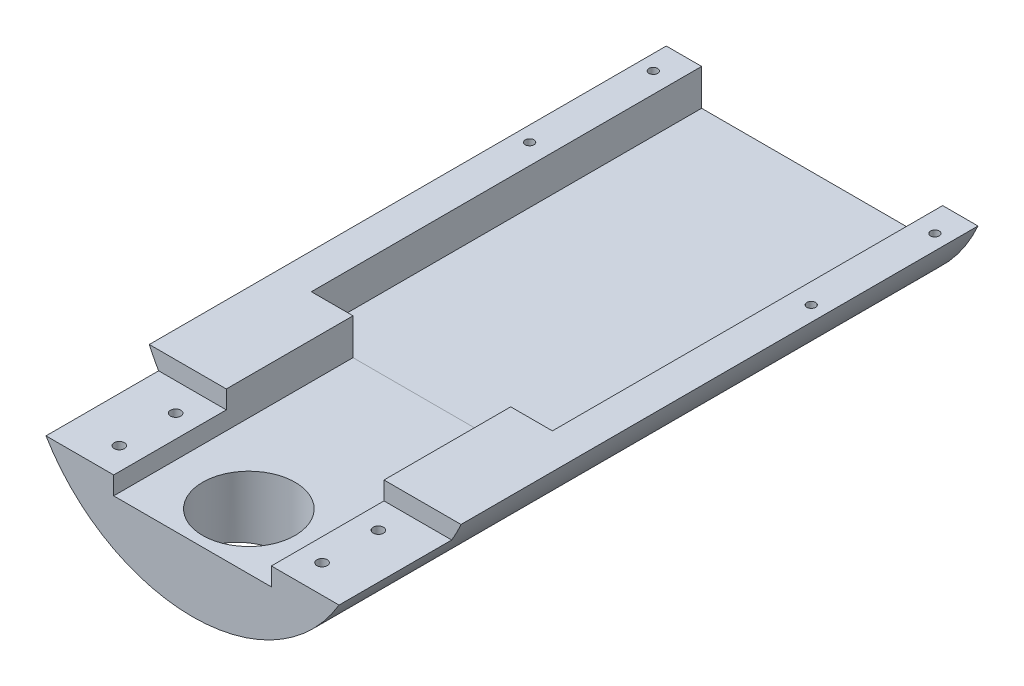
SolidWorks part; units mm, degrees
material "eSUN PLA+ (Not accurate)"
ref_plane "Front Plane" through (0, 0, 0) normal (0, 0, 1) x (1, 0, 0)
ref_plane "Top Plane" through (0, 0, 0) normal (0, 1, 0) x (1, 0, 0)
ref_plane "Right Plane" through (0, 0, 0) normal (1, 0, 0) x (0, 0, -1)
sketch "Sketch1" plane through (0, 0, 0) normal (0, 0, 1) x (1, 0, 0)
  line L0 (-69.1908, -30.525) -> (-35, -30.525)
  line L1 (-35, -30.525) -> (-35, -46.625)
  line L2 (-35, -46.625) -> (35, -46.625)
  line L3 (35, -46.625) -> (35, -30.525)
  line L4 (35, -30.525) -> (69.1908, -30.525)
  circle A0 centre (0, 0) radius 75.625 construction
  arc A1 (-69.1908, -30.525) -> (69.1908, -30.525) centre (0, 0) ccw
  point P10 (0, -75.625)
  dimension "D1" = 151.25
  dimension "D2" = 70
  dimension "D3" = 29
  dimension "D4" = 16.1
extrude "Boss-Extrude1" add sketch "Sketch1" along normal blind 279.5 from offset 15
sketch "Sketch2" plane through (0, 0, 294.5) normal (0, 0, 1) x (1, 0, 0)
  line L0 (-35, -30.525) -> (-35, -38.575) construction
  line L1 (-35, -46.625) -> (-35, -30.525) construction
  line L2 (-35, -38.575) -> (-35, -46.625) construction
  line L3 (-35, -30.525) -> (-35, -38.575)
  line L6 (-35, -38.575) -> (-65.047, -38.575)
  line L8 (-69.1908, -30.525) -> (-35, -30.525)
  arc A0 (-69.1908, -30.525) -> (-65.047, -38.575) centre (0, 0) ccw
  arc A2 (-69.1908, -30.525) -> (69.1908, -30.525) centre (0, 0) ccw construction
sketch "Sketch3" plane through (0, 0, 15) normal (0, 0, -1) x (-1, 0, 0)
  line L0 (-35, -46.625) -> (35, -46.625) construction
  line L1 (53.5, 46.625) -> (-53.5, 46.625)
  line L2 (53.5, 46.625) -> (53.5, -46.625)
  line L3 (53.5, -46.625) -> (-53.5, -46.625)
  line L4 (-53.5, 46.625) -> (-53.5, -46.625)
  line L5 (53.5, 46.625) -> (-53.5, -46.625) construction
  line L6 (53.5, -46.625) -> (-53.5, 46.625) construction
  point P0 (0, 0)
  dimension "D1" = 107
extrude "Cut-Extrude1" cut sketch "Sketch3" against normal blind 173.25
sketch "Sketch4" plane through (0, -46.625, 0) normal (0, 1, 0) x (1, 0, 0)
  line L1 (0, -15) -> (0, -294.5) construction
  line L2 (53.5, -15) -> (-53.5, -15) construction
  line L3 (35, -294.5) -> (-35, -294.5) construction
  circle A0 centre (0, -269.5) radius 20.5
  dimension "D1" = 41
  dimension "D2" = 25
extrude "Cut-Extrude2" cut sketch "Sketch4" against normal through all
extrude "Cut-Extrude3" cut sketch "Sketch2" against normal blind 50
sketch "Sketch6" plane through (0, 0, 294.5) normal (0, 0, 1) x (1, 0, 0)
  line L0 (-42.2865, -46.625) -> (-59.542, -46.625)
  line L1 (-59.542, -46.625) -> (-42.2865, -46.625)
  line L2 (-42.2865, -46.625) -> (-42.2865, -62.6976)
  arc A0 (-59.542, -46.625) -> (-42.2865, -62.6976) centre (0, 0) ccw
  arc A1 (-65.047, -38.575) -> (69.1908, -30.525) centre (0, 0) ccw construction
mirror "Mirror1" about plane through (0, 0, 0) normal (1, 0, 0) of "Cut-Extrude3"
sketch "Sketch7" plane through (0, -38.575, 0) normal (0, 1, 0) x (1, 0, 0)
  line L1 (35, -269.5) -> (65.047, -269.5) construction
  line L4 (35, -294.5) -> (65.047, -294.5)
  line L5 (65.047, -294.5) -> (65.047, -244.5)
  line L6 (65.047, -244.5) -> (35, -244.5)
  line L7 (35, -244.5) -> (35, -294.5)
  line L8 (35, -294.5) -> (65.047, -294.5) construction
  line L9 (65.047, -294.5) -> (65.047, -244.5) construction
  line L10 (65.047, -244.5) -> (35, -244.5) construction
  line L11 (35, -244.5) -> (35, -294.5) construction
  circle A0 centre (45, -257) radius 2.3
  circle A1 centre (45, -282) radius 2.3
  dimension "D2" = 4.6
  dimension "D3" = 25
  dimension "D4" = 10
  dimension "D1" = 0
extrude "Cut-Extrude5" cut sketch "Sketch7" against normal through all
mirror "Mirror2" about plane through (0, 0, 0) normal (1, 0, 0) of "Cut-Extrude5"
ref_plane "Plane1" through (0, -52.075, 0) normal (0, 1, 0) x (1, 0, 0)
sketch "Sketch11" plane through (0, -52.075, 0) normal (0, 1, 0) x (1, 0, 0)
  circle A0 centre (45, -257) radius 2.3 construction
  circle A1 centre (45, -282) radius 2.3 construction
  circle A2 centre (45, -257) radius 2.3 construction
  circle A3 centre (45, -282) radius 2.3 construction
  circle A4 centre (45, -282) radius 3.8
  circle A5 centre (45, -257) radius 3.8
  dimension "D1" = 7.6
ref_plane "Plane2" through (0, 0, 154.5) normal (0, 0, 1) x (1, 0, 0)
other "Intersect1" [suppressed]
move or copy body "Body-Convert to Mesh Body2" [suppressed] bodies to move or copy 114 copy no translate (0, 0, 0)
sketch "Sketch13" plane through (0, -46.625, 0) normal (0, 1, 0) x (1, 0, 0)
  line L0 (35, -188.25) -> (-35, -188.25)
  line L1 (-35, -294.5) -> (-35, -188.25) construction
  line L2 (-35, -188.25) -> (-53.5, -188.25) construction
split line "Split Line1"
extrude "Cut-Extrude8" cut sketch "Sketch11" along normal blind 7 and the other way through all
mirror "Mirror3" about plane through (0, 0, 0) normal (1, 0, 0) of "Cut-Extrude8"
sketch "Sketch14" plane through (0, -30.525, 0) normal (0, 1, 0) x (1, 0, 0)
  circle A0 centre (62.5, -82.35) radius 1.875 construction
  circle A1 centre (62.5, -27.45) radius 1.875 construction
  circle A2 centre (62.5, -82.35) radius 1.875 construction
  circle A3 centre (62.5, -27.45) radius 1.875 construction
  circle A5 centre (62.5, -27.45) radius 1.93
  circle A6 centre (62.5, -82.35) radius 1.93
  dimension "D1" = 3.86
extrude "Cut-Extrude9" cut sketch "Sketch14" against normal blind 7.25
mirror "Mirror4" about plane through (0, 0, 0) normal (1, 0, 0) of "Cut-Extrude9"
ref_plane "Plane3" through (0, 0, 87) normal (0, 0, 1) x (1, 0, 0)
other "Intersect2" [suppressed]
move or copy body "Body-Convert to Mesh Body3" [suppressed] bodies to move or copy 122 copy no translate (0, 0, 0) parameters "D1"=0, "D2"=0, "D3"=0
sketch "Sketch18" plane through (0, 0, 15) normal (0, 0, -1) x (-1, 0, 0)
  line L0 (0, -56.625) -> (0, -46.625)
  line L1 (0, -75.625) -> (0, -56.625) construction
  line L4 (-53.5, -46.625) -> (53.5, -46.625) construction
  line L13 (42.2078, -56.625) -> (-42.2078, -56.625)
  line L14 (42.2078, -56.625) -> (-42.2078, -56.625)
  line L17 (-44.3364, -50.125) -> (44.3364, -50.125)
  line L19 (44.3364, -56.125) -> (-44.3364, -56.125)
  line L20 (-44.3364, -56.125) -> (-44.3364, -50.125)
  line L21 (44.3364, -56.125) -> (44.3364, -50.125)
  line L27 (28.4868, -64.625) -> (-28.4868, -64.625) construction
  line L28 (30.1174, -64.625) -> (-30.1174, -64.625)
  arc A0 (-44.3364, -56.125) -> (44.3364, -56.125) centre (0, 1.8987) ccw
  arc A12 (-42.2078, -56.625) -> (42.2078, -56.625) centre (0, 0) ccw
  arc A15 (-42.2078, -56.625) -> (42.2078, -56.625) centre (0, 0) ccw
  arc A26 (-69.1908, -30.525) -> (69.1908, -30.525) centre (0, 0) ccw construction
  point P3 (0, -71.125)
  point P4 (0, -70.625)
  dimension "D6" = 0.5
  dimension "D7" = 1.8987
  dimension "D8" = 0.5
  dimension "D9" = 6
  dimension "D3" = 0
extrude "Cut-Extrude10" cut sketch "Sketch18" against normal blind 125.5 contours L20 L19 L0 L17 | L19 L21 L17 L0 | L1 L28 A15 L14 | L28 L1 L14 A15 | A15 L28 A0 L19 L0 L14 | A15 L14 L0 L19 A0 L28
ref_plane "Plane4" through (0, 0, 40) normal (0, 0, -1) x (-1, 0, 0)
sketch "Sketch19" plane through (0, 0, 40) normal (0, 0, -1) x (-1, 0, 0)
  line L0 (30.1174, -64.625) -> (-30.1174, -64.625) construction
  line L1 (30.1174, -64.625) -> (-30.1174, -64.625)
  arc A0 (-44.3364, -56.125) -> (44.3364, -56.125) centre (0, 1.8987) ccw construction
  arc A1 (-44.3364, -56.125) -> (44.3364, -56.125) centre (0, 1.8987) ccw
extrude "Cut-Extrude12" cut sketch "Sketch19" against normal blind 100.5 contours L1 A1
ref_plane "Plane5" through (0, 0, 65) normal (0, 0, -1) x (-1, 0, 0)
sketch "Sketch20" plane through (0, 0, 65) normal (0, 0, -1) x (-1, 0, 0)
  line L0 (-44.3364, -56.125) -> (-44.3364, -50.125) construction
  line L1 (44.3364, -56.125) -> (-44.3364, -56.125) construction
  line L2 (44.3364, -56.125) -> (44.3364, -50.125) construction
  line L3 (-44.3364, -50.125) -> (44.3364, -50.125) construction
  line L4 (-44.3364, -56.125) -> (-44.3364, -50.125)
  line L5 (44.3364, -56.125) -> (-44.3364, -56.125)
  line L6 (44.3364, -56.125) -> (44.3364, -50.125)
  line L7 (-44.3364, -50.125) -> (44.3364, -50.125)
extrude "Boss-Extrude2" add sketch "Sketch20" against normal up to surface (75.5 mm away) up to face at (0, -56.875, 140.5)
sketch "screw head hole" plane through (0, 0, 15) normal (0, 0, -1) x (-1, 0, 0)
  circle A0 centre (0, -68.825) radius 1.45 construction
  circle A1 centre (0, -68.825) radius 1.45
  circle A2 centre (0, -68.825) radius 3.3
  dimension "D1" = 6.6
extrude "Cut-Extrude13" cut sketch "screw head hole" against normal blind 7 contours A1 | A2 A1
equation "\"4mmmm\"= 3.85"
equation "\"8mmmm\"=6.4"
equation "\"D1@Boss-Extrude3@Connection Idea<1>.Part\" = \"totExtrusion@Connection Idea<1>.Part\""
equation "\"D1@Cut-Extrude10\" = \"totExtrusion@Connection Idea<1>.Part\" + \"extraSpaceForBigExt\""
equation "\"lockHolder\"= 25mm"
equation "\"D1@Cut-Extrude12\" = \"totExtrusion@Connection Idea<1>.Part\" + \"extraSpaceForBigExt\" - \"lockHolder\""
equation "\"extraSpaceForBigExt\"= 0.5mm"
equation "\"D8@Sketch18\"=\"D6@Sketch18\""
